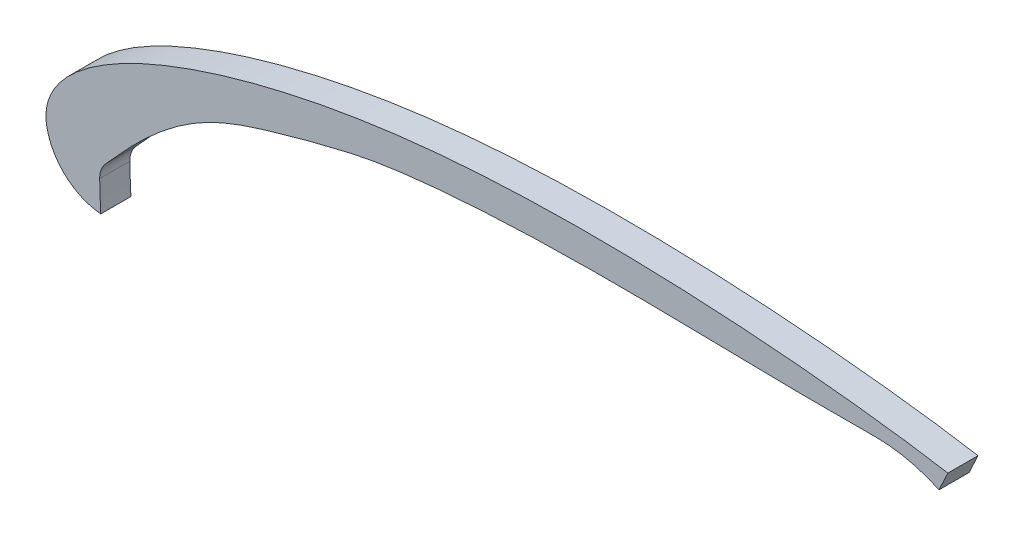
SolidWorks part; units mm, degrees
ref_plane "Přední rovina" through (0, 0, 0) normal (0, 0, 1) x (1, 0, 0)
ref_plane "Horní rovina" through (0, 0, 0) normal (0, 1, 0) x (1, 0, 0)
ref_plane "Pravá rovina" through (0, 0, 0) normal (1, 0, 0) x (0, 0, -1)
sketch "Skica1" plane through (0, 0, 0) normal (0, 0, 1) x (1, 0, 0)
  line L0 (0, 10) -> (-5, 10)
  line L1 (4.2262, 9.0631) -> (4.8128, 10.3211)
  line L2 (0, 0) -> (-51.4922, -0.8988) construction
  line L3 (-2.755, -11.0498) -> (-2.4192, -9.703) construction
  line L4 (0, 0) -> (9.5355, 0) construction
  line L5 (-48.6269, -32.4626) -> (-61.082, 31.6131) construction
  arc A0 (4.2262, 9.0631) -> (0, 10) centre (0, 0) ccw
  arc A1 (9.1735, 3.9807) -> (0, 10) centre (0, 0) ccw construction
  arc A2 (-51.0714, 0.1694) -> (-51.4922, -0.8988) centre (-49.9924, -0.8726) ccw
  arc A3 (-51.4922, -0.8988) -> (-51.4184, -2.8978) centre (0, 0) ccw
  arc A4 (-55, 0.324) -> (-51.4184, -2.8978) centre (-51.0735, 1.0873) ccw
  spline S0 degree 3 poles (4.8128, 10.3211) (-0.4395, 11.2472) (-32.098, 15.081) (-55.954, 5.2322) (-55, 0.324) knots 0 0 0 0 0.525666 0.98526 0.98526 0.98526 0.98526
  spline S1 degree 3 poles (21.817, 6.5947) (16.5674, 8.0618) (10.8721, 9.2527) (4.8128, 10.3211) knots 0.509175 0.509175 0.509175 0.509175 0.766374 0.766374 0.766374 0.766374 construction
  spline S2 degree 3 poles (-5, 10) (-8.3333, 10) (-20.4831, 10.4806) (-31.5456, 9.6349) (-34.7956, 8.8941) knots 0 0 0 0 0.534032 1 1 1 1
  spline S4 degree 3 poles (1979.9503, -115.197) (205.352, -85.6344) (56.3806, 19.6252) (-29.1156, 10.051) (-32.4136, 9.4705) (-36.5276, 8.4842) (-37.35, 8.2739) (-38.5856, 7.9388) (-38.9978, 7.8238) (-39.8233, 7.5871) (-40.2365, 7.4663) (-41.4922, 7.0823) (-42.3422, 6.7988) (-43.5873, 6.2781) (-44, 6.086) (-44.7884, 5.6733) (-45.1657, 5.4536) (-46.9686, 4.3109) (-48.1452, 3.2558) (-49.5376, 1.853) (-49.9397, 1.4147) (-50.4451, 0.8551) (-50.5973, 0.6849) (-57.8172, -7.2963) (-14.5966, 46.7716) (1136.4706, 1609.271) knots -5.76057 -5.76057 -5.76057 -5.76057 0.25 0.25 0.5 0.5 0.5625 0.5625 0.59375 0.59375 0.625 0.625 0.6875 0.6875 0.71875 0.71875 0.75 0.75 0.875 0.875 0.9375 0.9375 0.96875 0.96875 2.624314 2.624314 2.624314 2.624314 only from (-15, 10.9999) to (-51.0714, 0.1694)
  spline S5 degree 3 poles (-34.7956, 8.8941) (-35.0988, 8.825) (-35.4018, 8.7541) (-36.5276, 8.4842) (-37.35, 8.2739) (-38.5856, 7.9388) (-38.9978, 7.8238) (-39.8233, 7.5871) (-40.2365, 7.4663) (-41.4922, 7.0823) (-42.3422, 6.7988) (-43.5873, 6.2781) (-44, 6.086) (-44.7884, 5.6733) (-45.1657, 5.4536) (-46.9686, 4.3109) (-48.1452, 3.2558) (-49.5376, 1.853) (-49.9397, 1.4147) (-50.4451, 0.8551) (-50.5973, 0.6849) (-50.8648, 0.3892) (-50.9806, 0.2634) (-51.0714, 0.1694) knots 0.476985 0.476985 0.476985 0.476985 0.5 0.5 0.5625 0.5625 0.59375 0.59375 0.625 0.625 0.6875 0.6875 0.71875 0.71875 0.75 0.75 0.875 0.875 0.9375 0.9375 0.96875 0.96875 1 1 1 1
  dimension "D4" = 4
  dimension "D7" = 15
  dimension "D8" = 16
  dimension "D13" = 10
  dimension "D14" = 10
  dimension "D1" = 65
  dimension "D2" = 5
  dimension "D5" = 55
  dimension "D6" = 2
  dimension "D9" = 12
  dimension "D10" = 9.5
  dimension "D11" = 32
  dimension "D12" = 100
  dimension "D15" = 10.5
  dimension "D16" = 21
  dimension "D3" = 1.5
extrude "Přidat vysunutím1" add sketch "Skica1" along normal mid plane 2
